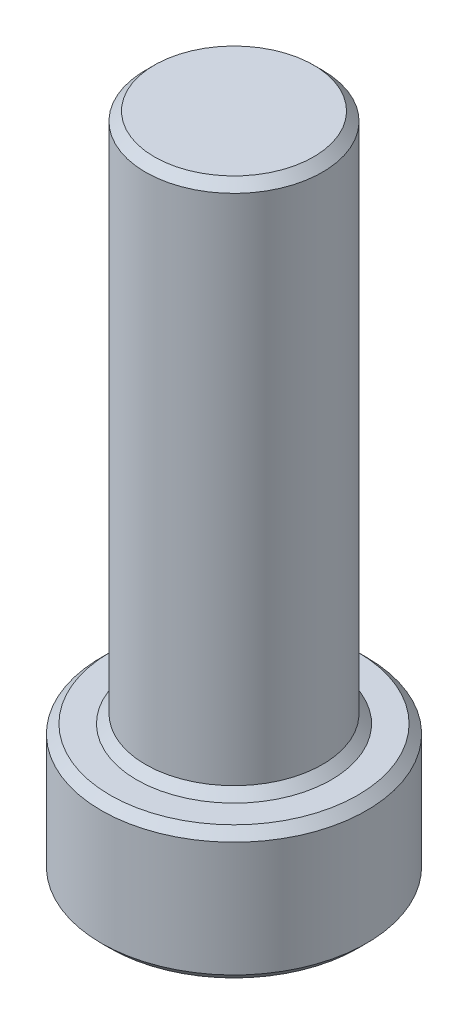
SolidWorks part; units mm, degrees
ref_plane "Plan de face" through (0, 0, 0) normal (0, 0, 1) x (1, 0, 0)
ref_plane "Plan de dessus" through (0, 0, 0) normal (0, 1, 0) x (1, 0, 0)
ref_plane "Plan de droite" through (0, 0, 0) normal (1, 0, 0) x (0, 0, -1)
sketch "Esquisse1" plane through (0, 0, 0) normal (0, 1, 0) x (1, 0, 0)
  circle A0 centre (0, 0) radius 3
  dimension "D1" = 6
extrude "Boss.-Extru.1" add sketch "Esquisse1" along normal blind 3
sketch "Esquisse2" plane through (0, 3, 0) normal (0, 1, 0) x (1, 0, 0)
  circle A0 centre (0, 0) radius 2
  dimension "D1" = 4
extrude "Boss.-Extru.2" add sketch "Esquisse2" along normal blind 12
sketch "Esquisse3" plane through (0, 0, 0) normal (0, -1, 0) x (1, 0, 0)
  circle A0 centre (0, 0) radius 1.65
  dimension "D1" = 3.3
extrude "Enlèv. mat.-Extru.1" cut sketch "Esquisse3" against normal blind 2
chamfer "Chanfrein1" distance 0.2 angle 45 5 edges at (0, 3, 2) (0, 3, 3) (0, 0, -1.65) (0, 0, 3) (0, 15, 2)
